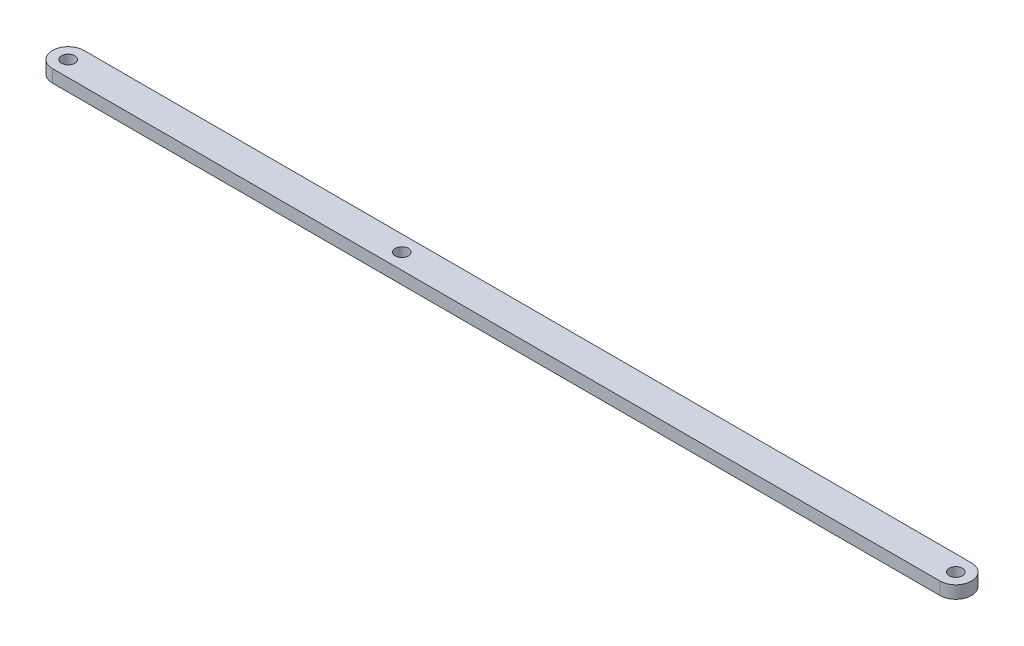
SolidWorks part; units mm, degrees
ref_plane "Front Plane" through (0, 0, 0) normal (0, 0, 1) x (1, 0, 0)
ref_plane "Top Plane" through (0, 0, 0) normal (0, 1, 0) x (1, 0, 0)
ref_plane "Right Plane" through (0, 0, 0) normal (1, 0, 0) x (0, 0, -1)
sketch "Sketch1" plane through (0, 0, 0) normal (0, 1, 0) x (1, 0, 0)
  line L0 (0, 0) -> (141, 0) construction
  line L1 (0, 2.5) -> (141, 2.5)
  line L2 (0, -2.5) -> (141, -2.5)
  arc A0 (0, 2.5) -> (0, -2.5) centre (0, 0) ccw
  arc A1 (141, -2.5) -> (141, 2.5) centre (141, 0) ccw
  circle A2 centre (0, 0) radius 1.05
  circle A3 centre (141, 0) radius 1.05
  circle A4 centre (53, 0) radius 1.05
  point P3 (70.5, 0)
  dimension "D1" = 2.5
  dimension "D3" = 2.1
  dimension "D4" = 2.1
  dimension "D5" = 2.1
  dimension "D2" = 141
  dimension "D6" = 53
extrude "Boss-Extrude1" add sketch "Sketch1" along normal blind 2
